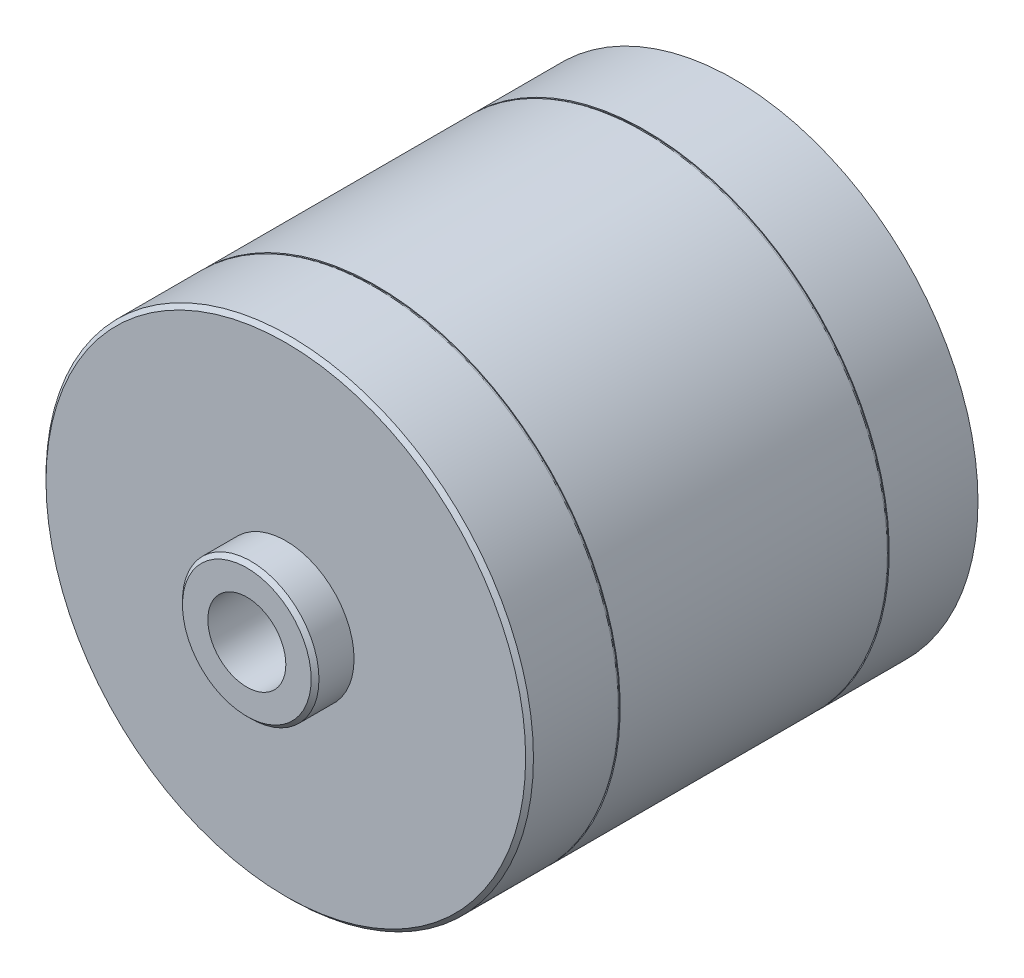
SolidWorks part; units mm, degrees
ref_plane "Alzado" through (0, 0, 0) normal (0, 0, 1) x (1, 0, 0)
ref_plane "Planta" through (0, 0, 0) normal (0, 1, 0) x (1, 0, 0)
ref_plane "Vista lateral" through (0, 0, 0) normal (1, 0, 0) x (0, 0, -1)
sketch "Croquis1" plane through (0, 0, 0) normal (0, 0, 1) x (1, 0, 0)
  circle A0 centre (0, 0) radius 12.5
  dimension "D1" = 25
extrude "Saliente-Extruir1" add sketch "Croquis1" along normal blind 23
sketch "Croquis2" plane through (0, 0, 23) normal (0, 0, 1) x (1, 0, 0)
  circle A0 centre (0, 0) radius 3.5
  dimension "D1" = 7
extrude "Saliente-Extruir2" add sketch "Croquis2" along normal blind 2
sketch "Croquis3" plane through (0, 0, 25) normal (0, 0, 1) x (1, 0, 0)
  circle A0 centre (0, 0) radius 2
  dimension "D1" = 4
extrude "Cortar-Extruir2" cut sketch "Croquis3" against normal blind 6
chamfer "Chaflán2" distance 0.2 angle 45 1 edges at (12.5, 0, 23)
sketch "Croquis4" plane through (0, 0, 0) normal (0, 1, 0) x (1, 0, 0)
  line L0 (0, 0) -> (0, -23.5707) construction
  line L1 (-12.5, 0) -> (-12.5, -22.8) construction
  line L2 (-12.55, -4.65) -> (-12.45, -4.65)
  line L3 (-12.55, -4.65) -> (-12.55, -4.55)
  line L4 (-12.55, -4.55) -> (-12.45, -4.55)
  line L5 (-12.45, -4.65) -> (-12.45, -4.55)
  line L6 (-12.55, -4.65) -> (-12.45, -4.55) construction
  line L7 (-12.55, -4.55) -> (-12.45, -4.65) construction
  line L8 (-12.3, -23) -> (12.3, -23) construction
  line L9 (-12.55, -18.45) -> (-12.45, -18.45)
  line L10 (-12.55, -18.45) -> (-12.55, -18.35)
  line L11 (-12.55, -18.35) -> (-12.45, -18.35)
  line L12 (-12.45, -18.45) -> (-12.45, -18.35)
  line L13 (-12.55, -18.45) -> (-12.45, -18.35) construction
  line L14 (-12.55, -18.35) -> (-12.45, -18.45) construction
  line L15 (12.5, 0) -> (-12.5, 0) construction
  point P3 (-12.5, -4.6)
  point P10 (-12.5, -18.4)
  dimension "D1" = 0.1
  dimension "D2" = 0.1
  dimension "D3" = 0.1
  dimension "D4" = 0.1
  dimension "D5" = 4.6
  dimension "D6" = 4.6
revolve "Cortar-Revolución1" cut sketch "Croquis4" angle 360 about L0
chamfer "Chaflán3" distance 0.2 angle 45 1 edges at (3.5, 0, 25)
